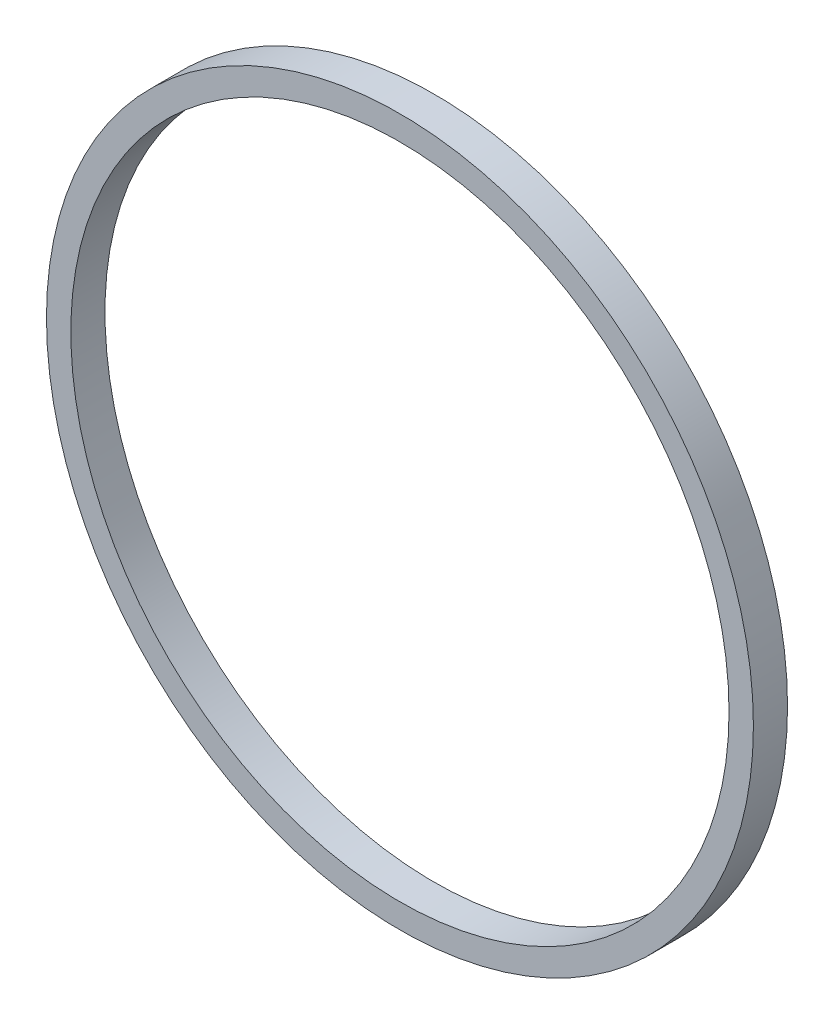
SolidWorks part; units mm, degrees
material "ABS"
ref_plane "前视基准面" through (0, 0, 0) normal (0, 0, 1) x (1, 0, 0)
ref_plane "上视基准面" through (0, 0, 0) normal (0, 1, 0) x (1, 0, 0)
ref_plane "右视基准面" through (0, 0, 0) normal (1, 0, 0) x (0, 0, -1)
other "Configuration Table"
sketch "草图1" plane through (0, 0, 0) normal (0, 0, 1) x (1, 0, 0)
  circle A0 centre (0, 0) radius 13.5
  circle A1 centre (0, 0) radius 14.5
  dimension "D1" = 27
  dimension "D2" = 1
extrude "凸台-拉伸1" add sketch "草图1" along normal blind 1.4
